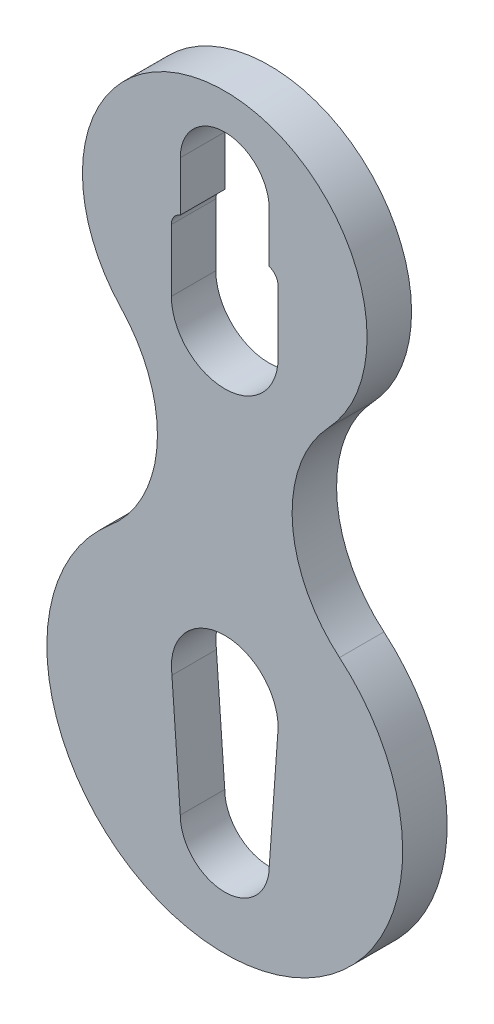
SolidWorks part; units mm, degrees
ref_plane "Front Plane" through (0, 0, 0) normal (0, 0, 1) x (1, 0, 0)
ref_plane "Top Plane" through (0, 0, 0) normal (0, 1, 0) x (1, 0, 0)
ref_plane "Right Plane" through (0, 0, 0) normal (1, 0, 0) x (0, 0, -1)
sketch "Sketch1" plane through (0, 0, 0) normal (0, 0, 1) x (1, 0, 0)
  line L0 (0, 0) -> (0, 485.4976) construction
  line L1 (-12, 10) -> (-10, -18)
  line L2 (12, 10) -> (10, -18)
  line L3 (-10, 110) -> (-10, 98.8284)
  line L6 (12, 96) -> (12, 82)
  line L7 (-12, 96) -> (-12, 82)
  line L8 (0, 82) -> (-12, 82) construction
  line L9 (10, 110) -> (10, 98.8284)
  line L10 (0, 82) -> (0, 106) construction
  line L11 (-22, 82) -> (-22, 106)
  line L12 (22, 82) -> (22, 106)
  arc A0 (11.8782, 8.2944) -> (-11.8782, 8.2944) centre (0, 10) ccw
  arc A1 (-10, -18) -> (10, -18) centre (0, -18) ccw
  arc A2 (-25.7951, 30.5714) -> (25.7951, 30.5714) centre (0, 0) ccw
  arc A5 (23.2988, 74.0645) -> (-23.2988, 74.0645) centre (0, 96) ccw
  arc A6 (-23.2988, 74.0645) -> (-25.7951, 30.5714) centre (-45.1414, 53.5) cw
  arc A7 (23.2988, 74.0645) -> (25.7951, 30.5714) centre (45.1414, 53.5) ccw
  arc A10 (10, 110) -> (-10, 110) centre (0, 110) ccw
  arc A11 (-12, 82) -> (12, 82) centre (0, 82) ccw
  arc A12 (-10, 98.8284) -> (-12, 96) centre (-9, 96) ccw
  arc A13 (10, 98.8284) -> (12, 96) centre (9, 96) cw
  arc A14 (-22, 82) -> (22, 82) centre (0, 82) ccw
  arc A15 (22, 106) -> (-22, 106) centre (0, 106) ccw
  point P19 (0, 94)
  point P38 (0, 0)
  point P39 (0, 0)
  dimension "D1" = 20
  dimension "D2" = 24
  dimension "D3" = 80
  dimension "D6" = 64
  dimension "D10" = 30
  dimension "D11" = 28
  dimension "D12" = 3
  dimension "D8" = 24
  dimension "D7" = 20
  dimension "D14" = 22
  dimension "D4" = 10
  dimension "D5" = 28
  dimension "D9" = 14
  dimension "D13" = 128
extrude "Boss-Extrude1" add sketch "Sketch1" along normal mid plane 10 contours L12 A15 L11 A14 L9 A13 L6 A11 L7 A12 L3 A10 | A15 L12 A14 L11 A5 A6 A2 A7 A1 L1 A0 L2
